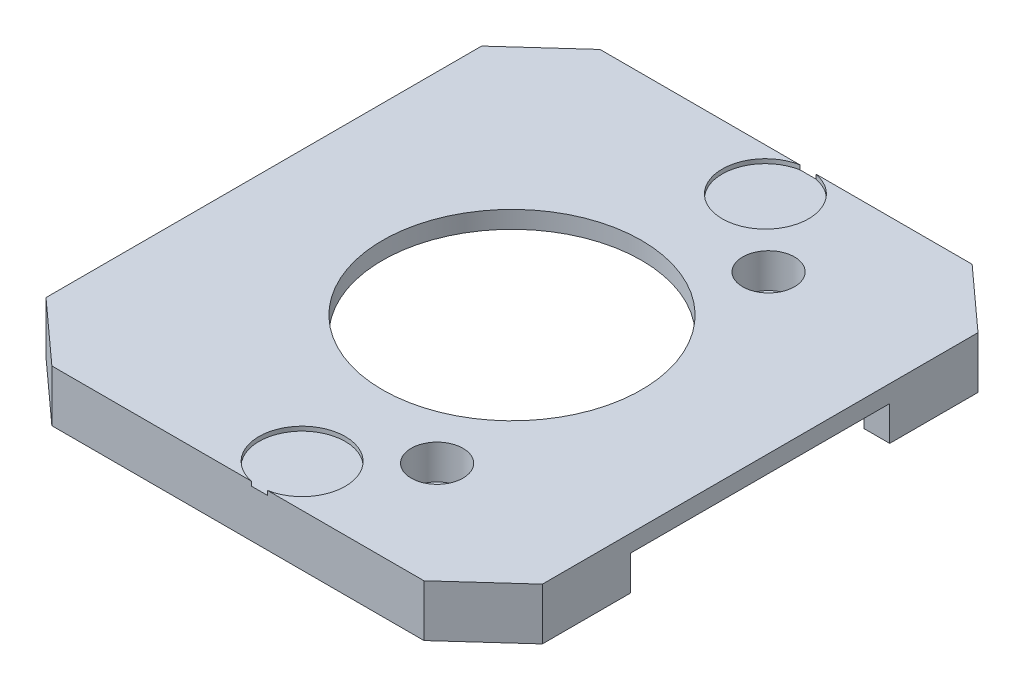
SolidWorks part; units mm, degrees
ref_plane "前视基准面" through (0, 0, 0) normal (0, 0, 1) x (1, 0, 0)
ref_plane "上视基准面" through (0, 0, 0) normal (0, 1, 0) x (1, 0, 0)
ref_plane "右视基准面" through (0, 0, 0) normal (1, 0, 0) x (0, 0, -1)
other "Configuration Table"
sketch "草图1" plane through (0, 0, 0) normal (0, 1, 0) x (1, 0, 0)
  line L0 (-47.2885, 0) -> (53.1842, 0) construction
  line L1 (-28.75, 31.75) -> (28.75, 31.75)
  line L2 (-28.75, 31.75) -> (-28.75, -31.75)
  line L3 (-28.75, -31.75) -> (28.75, -31.75)
  line L4 (28.75, 31.75) -> (28.75, -31.75)
  line L5 (-28.75, 31.75) -> (28.75, -31.75) construction
  line L6 (-28.75, -31.75) -> (28.75, 31.75) construction
  line L7 (-21.5504, 31.75) -> (-28.75, 25.2307)
  line L8 (28.75, -25.2307) -> (21.5504, -31.75)
  line L9 (-28.75, -25.2307) -> (-21.5504, -31.75)
  line L10 (21.5504, 31.75) -> (28.75, 25.2307)
  circle A0 centre (2.52, 26.835) radius 3
  circle A1 centre (2.52, -26.835) radius 3
  point P0 (0, 0)
  dimension "D3" = 6
  dimension "D1" = 63.5
  dimension "D2" = 57.5
  dimension "D4" = 53.67
  dimension "D5" = 26.23
  dimension "D6" = 90
  dimension "D7" = 90
  dimension "D8" = 38
  dimension "D9" = 38
  dimension "D10" = 38
  dimension "D11" = 38
extrude "凸台-拉伸1" add sketch "草图1" along normal blind 6 contours L10 L1 L7 L2 L9 L3 L8 L4 A0 A1
sketch "草图2" plane through (0, 6, 0) normal (0, 1, 0) x (1, 0, 0)
  line L0 (-36.289, 0) -> (36.289, 0) construction
  circle A0 centre (10.52, 19.2) radius 1.6
  circle A1 centre (10.52, -19.2) radius 1.6
  circle A3 centre (2.52, 26.835) radius 3 construction
  point P6 (0, 0)
  dimension "D1" = 3.2
  dimension "D2" = 8
  dimension "D3" = 38.4
extrude "切除-拉伸1" cut sketch "草图2" against normal blind 7
sketch "草图3" plane through (0, 6, 0) normal (0, 1, 0) x (1, 0, 0)
  circle A0 centre (10.52, -19.2) radius 1.6 construction
  circle A1 centre (10.52, 19.2) radius 1.6 construction
  circle A2 centre (10.52, -19.2) radius 1.6
  circle A3 centre (10.52, 19.2) radius 1.6
  circle A4 centre (10.52, 19.2) radius 3
  circle A5 centre (10.52, -19.2) radius 3
  dimension "D1" = 6
  dimension "D2" = 6
extrude "切除-拉伸2" cut sketch "草图3" against normal blind 4
sketch "草图5" plane through (0, 0, 0) normal (0, -1, 0) x (1, 0, 0)
  line L1 (7.1388, 26.835) -> (4.8294, 30.835)
  line L2 (4.8294, 30.835) -> (0.2106, 30.835)
  line L3 (0.2106, 30.835) -> (-2.0988, 26.835)
  line L4 (-2.0988, 26.835) -> (0.2106, 22.835)
  line L5 (0.2106, 22.835) -> (4.8294, 22.835)
  line L6 (4.8294, 22.835) -> (7.1388, 26.835)
  line L7 (7.1388, -26.835) -> (4.8294, -22.835)
  line L8 (4.8294, -22.835) -> (0.2106, -22.835)
  line L9 (0.2106, -22.835) -> (-2.0988, -26.835)
  line L10 (-2.0988, -26.835) -> (0.2106, -30.835)
  line L11 (0.2106, -30.835) -> (4.8294, -30.835)
  line L12 (4.8294, -30.835) -> (7.1388, -26.835)
  circle A0 centre (2.52, 26.835) radius 4 construction
  circle A2 centre (2.52, -26.835) radius 4 construction
extrude "切除-拉伸3" cut sketch "草图5" against normal blind 4
sketch "草图6" plane through (0, 6, 0) normal (0, 1, 0) x (1, 0, 0)
  circle A0 centre (2.52, 26.835) radius 5
  circle A1 centre (2.52, -26.835) radius 5
  dimension "D1" = 10
  dimension "D2" = 10
extrude "切除-拉伸4" cut sketch "草图6" against normal blind 0.5
sketch "草图7" plane through (0, 0, 0) normal (0, -1, 0) x (1, 0, 0)
  line L0 (20.3939, -28.75) -> (25.75, -23.9)
  line L1 (25.75, -23.9) -> (25.75, -15)
  line L2 (25.75, 23.9) -> (20.3939, 28.75)
  line L3 (20.3939, 28.75) -> (-20.3939, 28.75)
  line L4 (-20.3939, 28.75) -> (-25.75, 23.9)
  line L5 (-25.75, 23.9) -> (-25.75, 15)
  line L6 (-25.75, -23.9) -> (-20.3939, -28.75)
  line L7 (-20.3939, -28.75) -> (20.3939, -28.75)
  line L8 (21.5504, -31.75) -> (28.75, -25.2307)
  line L9 (28.75, -25.2307) -> (28.75, 25.2307)
  line L10 (28.75, 25.2307) -> (21.5504, 31.75)
  line L11 (21.5504, 31.75) -> (-21.5504, 31.75)
  line L12 (-21.5504, 31.75) -> (-28.75, 25.2307)
  line L13 (-28.75, 25.2307) -> (-28.75, -25.2307)
  line L14 (-28.75, -25.2307) -> (-21.5504, -31.75)
  line L15 (-21.5504, -31.75) -> (21.5504, -31.75)
  line L16 (21.5504, -31.75) -> (28.75, -25.2307)
  line L17 (28.75, -25.2307) -> (28.75, 25.2307)
  line L18 (28.75, 25.2307) -> (21.5504, 31.75)
  line L19 (21.5504, 31.75) -> (-21.5504, 31.75)
  line L20 (-21.5504, 31.75) -> (-28.75, 25.2307)
  line L21 (-28.75, 25.2307) -> (-28.75, -25.2307)
  line L22 (-28.75, -25.2307) -> (-21.5504, -31.75)
  line L23 (-21.5504, -31.75) -> (21.5504, -31.75)
  line L24 (-43.254, 0) -> (45.3085, 0) construction
  line L25 (-28.75, 15) -> (-25.75, 15)
  line L26 (-28.75, -15) -> (-25.75, -15)
  line L27 (-25.75, -15) -> (-25.75, -23.9)
  line L28 (-25.75, 23.9) -> (-25.75, -23.9) construction
  line L29 (25.75, 15) -> (25.75, 23.9)
  line L30 (25.75, -23.9) -> (25.75, 23.9) construction
  line L31 (25.75, 15) -> (28.75, 15)
  line L32 (25.75, -15) -> (28.75, -15)
  circle A0 centre (2.52, 26.835) radius 7.5
  circle A1 centre (10.52, 19.2) radius 3
  circle A2 centre (10.52, 19.2) radius 3
  circle A3 centre (10.52, -19.2) radius 3
  circle A4 centre (10.52, -19.2) radius 3
  circle A5 centre (10.52, -19.2) radius 1.6
  circle A6 centre (10.52, -19.2) radius 1.6
  circle A7 centre (10.52, 19.2) radius 1.6
  circle A8 centre (10.52, 19.2) radius 1.6
  circle A9 centre (2.52, -26.835) radius 7.5
  circle A10 centre (10.52, 19.2) radius 6
  circle A11 centre (10.52, -19.2) radius 6
  dimension "D6" = 15
  dimension "D7" = 15
  dimension "D10" = 3
  dimension "D9" = 30
  dimension "D1" = 0
  dimension "D2" = 0
  dimension "D3" = 0
  dimension "D4" = 0
  dimension "D5" = 0
  dimension "D8" = 3
extrude "切除-拉伸6" cut sketch "草图7" against normal blind 4 contours A11 A9 L7 L0 L1 L32 L17 L31 L29 L2 L3 A0 A10 L4 L5 L25 L21 L26 L27 L6
sketch "草图8" plane through (0, 5.5, 0) normal (0, 1, 0) x (1, 0, 0)
  circle A0 centre (2.52, 26.835) radius 3 construction
  circle A1 centre (2.52, -26.835) radius 3 construction
  circle A2 centre (2.52, 26.835) radius 3
  circle A3 centre (2.52, -26.835) radius 3
extrude "凸台-拉伸2" add sketch "草图8" against normal blind 0.5
sketch "草图9" plane through (0, 2, 0) normal (0, 1, 0) x (1, 0, 0)
  circle A0 centre (10.52, -19.2) radius 1.6 construction
  circle A1 centre (10.52, 19.2) radius 1.6 construction
  circle A2 centre (10.52, -19.2) radius 1.6
  circle A3 centre (10.52, 19.2) radius 1.6
extrude "凸台-拉伸3" add sketch "草图9" against normal blind 0.5
sketch "草图10" plane through (0, 4, 0) normal (0, -1, 0) x (1, 0, 0)
  circle A0 centre (0, 0) radius 15
  dimension "D1" = 30
extrude "切除-拉伸7" cut sketch "草图10" against normal through all
